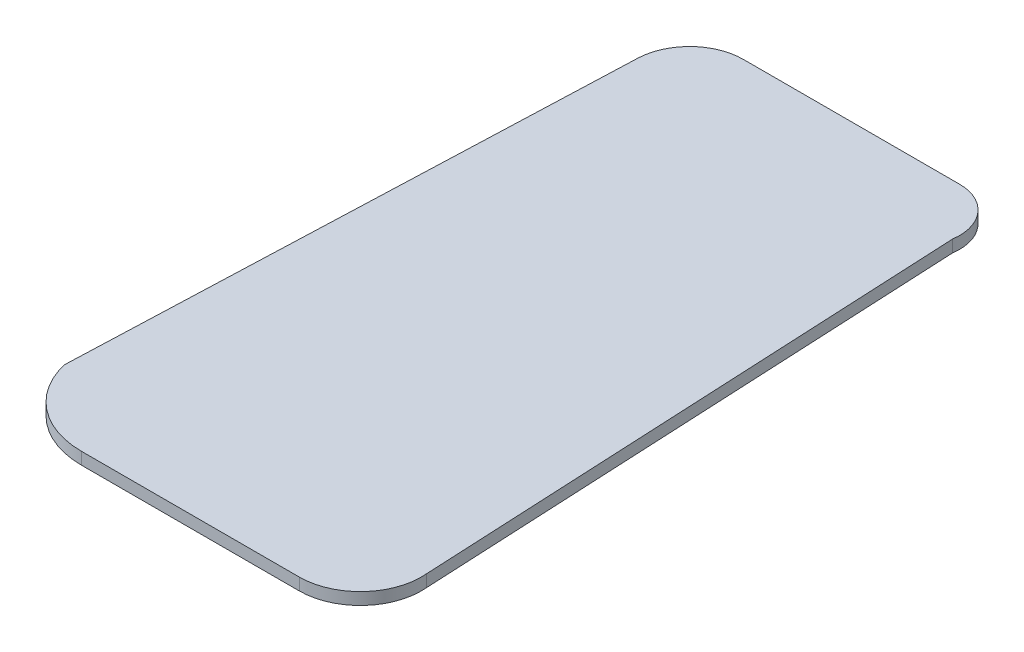
SolidWorks part; units mm, degrees
ref_plane "Front Plane" through (0, 0, 0) normal (0, 0, 1) x (1, 0, 0)
ref_plane "Top Plane" through (0, 0, 0) normal (0, 1, 0) x (1, 0, 0)
ref_plane "Right Plane" through (0, 0, 0) normal (1, 0, 0) x (0, 0, -1)
sketch "Sketch2" plane through (0, 0, 0) normal (0, 1, 0) x (1, 0, 0)
  line L4 (7.2371, 17.386) -> (11.7071, 133.9015)
  line L5 (70.7098, 3.3803) -> (24.8188, 3.3803)
  line L6 (77.8616, 133.9015) -> (83.5235, 17.386)
  line L7 (23.0308, 144.6293) -> (68.6238, 144.6293)
  arc A4 (70.7098, 3.3803) -> (83.5235, 17.386) centre (70.7098, 16.2448) ccw
  arc A5 (68.6238, 144.6293) -> (77.8616, 133.9015) centre (68.6238, 135.288) cw
  arc A6 (24.8188, 3.3803) -> (7.2371, 17.386) centre (24.8188, 21.4184) cw
  arc A7 (23.0308, 144.6293) -> (11.7071, 133.9015) centre (23.0308, 133.289) ccw
extrude "Boss-Extrude1" add sketch "Sketch2" along normal blind 2.54
